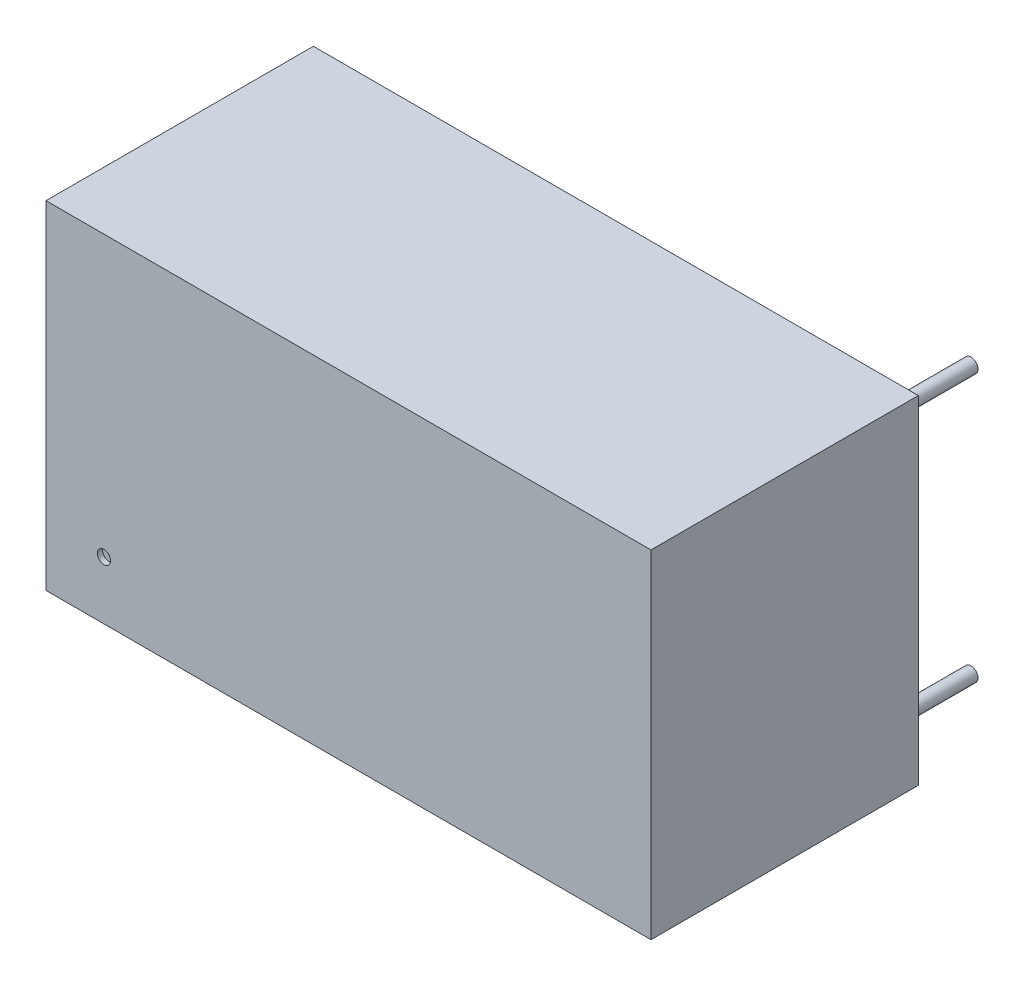
SolidWorks part; units mm, degrees
ref_plane "Ebene vorne" through (0, 0, 0) normal (0, 0, 1) x (1, 0, 0)
ref_plane "Ebene oben" through (0, 0, 0) normal (0, 1, 0) x (1, 0, 0)
ref_plane "Ebene rechts" through (0, 0, 0) normal (1, 0, 0) x (0, 0, -1)
sketch "Skizze1" plane through (0, 0, 0) normal (0, 0, 1) x (1, 0, 0)
  line L1 (0, 0) -> (34.48, 0)
  line L2 (0, 0) -> (0, 19.24)
  line L3 (0, 19.24) -> (34.48, 19.24)
  line L4 (34.48, 0) -> (34.48, 19.24)
  dimension "D1" = 19.24
  dimension "D2" = 34.48
extrude "Aufsatz-Linear austragen1" add sketch "Skizze1" along normal blind 15.24
sketch "Skizze2" plane through (0, 0, 15.24) normal (0, 0, 1) x (1, 0, 0)
  line L0 (0, 19.24) -> (0, 0) construction
  line L1 (0, 0) -> (34.48, 0) construction
  circle A0 centre (3.3, 3.3) radius 0.375
  dimension "D3" = 0.75
  dimension "D1" = 3.3
  dimension "D2" = 3.3
extrude "Schnitt-Linear austragen1" cut sketch "Skizze2" against normal blind 0.3
sketch "Skizze3" plane through (0, 0, 0) normal (0, 0, -1) x (-1, 0, 0)
  line L0 (-34.48, 19.24) -> (0, 19.24) construction
  line L1 (-34.48, 0) -> (-34.48, 19.24) construction
  line L2 (0, 0) -> (-34.48, 0) construction
  circle A0 centre (-32.48, 17.24) radius 0.4
  circle A1 centre (-32.48, 2) radius 0.4
  circle A2 centre (-2, 12.16) radius 0.4
  circle A3 centre (-2, 7.08) radius 0.4
  point P8 (0, 0)
  point P9 (0, 0)
  dimension "D1" = 0.8
  dimension "D3" = 2
  dimension "D4" = 2
  dimension "D5" = 30.48
  dimension "D2" = 2
  dimension "D6" = 7.08
  dimension "D7" = 7.08
extrude "Aufsatz-Linear austragen2" add sketch "Skizze3" along normal blind 5
